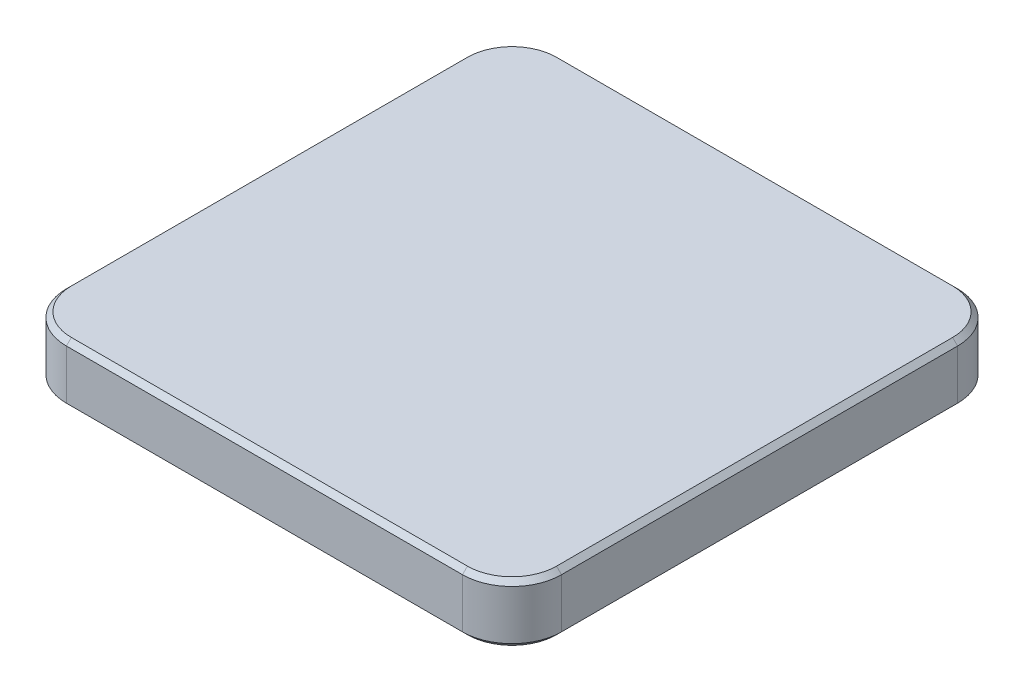
SolidWorks part; units mm, degrees
material "AISI 1020"
ref_plane "Alzado" through (0, 0, 0) normal (0, 0, 1) x (1, 0, 0)
ref_plane "Planta" through (0, 0, 0) normal (0, 1, 0) x (1, 0, 0)
ref_plane "Vista lateral" through (0, 0, 0) normal (1, 0, 0) x (0, 0, -1)
sketch "Croquis1" plane through (0, 0, 0) normal (0, 1, 0) x (1, 0, 0)
  line L1 (-50, -50) -> (50, -50)
  line L2 (-50, -50) -> (-50, 50)
  line L3 (-50, 50) -> (50, 50)
  line L4 (50, -50) -> (50, 50)
  line L5 (-50, -50) -> (50, 50) construction
  line L6 (-50, 50) -> (50, -50) construction
  point P0 (0, 0)
  dimension "D1" = 100
extrude "Saliente-Extruir1" add sketch "Croquis1" along normal blind 12
fillet "Redondeo1" radius 10 4 edges at (-50, 6, -50) (50, 6, -50) (-50, 6, 50) (50, 6, 50)
chamfer "Chaflán1" distance 1 angle 45 8 edges at (0, 12, -50) (-47.0711, 12, -47.0711) (47.0711, 12, -47.0711) (-50, 12, 0) (50, 12, 0) (-47.0711, 12, 47.0711) (47.0711, 12, 47.0711) (0, 12, 50)
chamfer "Chaflán2" distance 1 angle 45 8 edges at (-50, 0, 0) (-47.0711, 0, 47.0711) (-47.0711, 0, -47.0711) (0, 0, 50) (0, 0, -50) (47.0711, 0, 47.0711) (47.0711, 0, -47.0711) (50, 0, 0)
